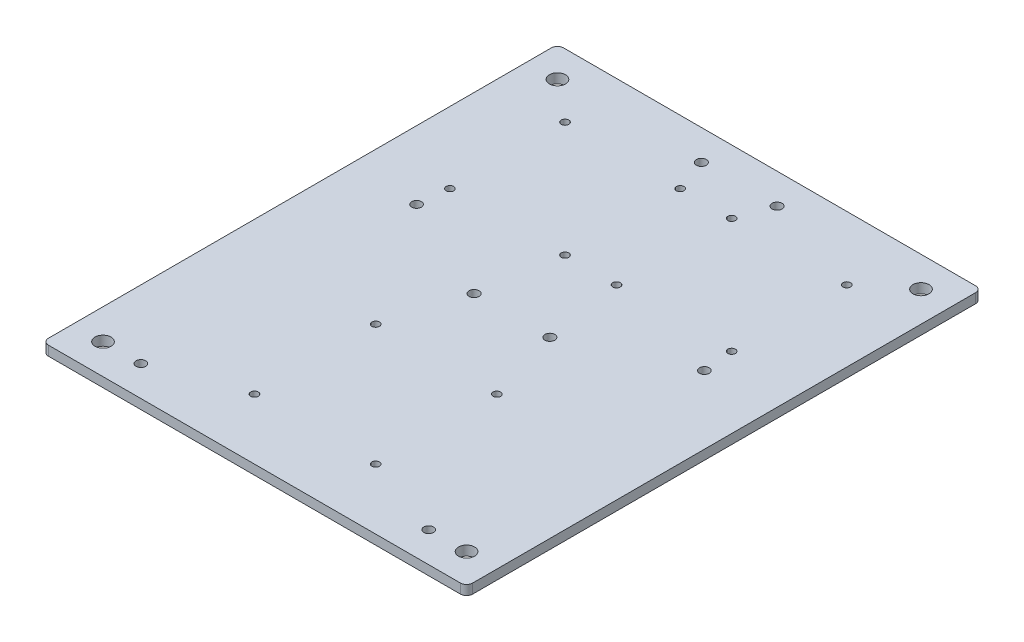
SolidWorks part; units mm, degrees
material "6061 Alloy"
ref_plane "Front Plane" through (0, 0, 0) normal (0, 0, 1) x (1, 0, 0)
ref_plane "Top Plane" through (0, 0, 0) normal (0, 1, 0) x (1, 0, 0)
ref_plane "Right Plane" through (0, 0, 0) normal (1, 0, 0) x (0, 0, -1)
sketch "Sketch1" plane through (0, 0, 0) normal (0, 1, 0) x (1, 0, 0)
  line L1 (-70, -85) -> (70, -85)
  line L2 (-70, -85) -> (-70, 85)
  line L3 (-70, 85) -> (70, 85)
  line L4 (70, -85) -> (70, 85)
  line L5 (-70, -85) -> (70, 85) construction
  line L6 (-70, 85) -> (70, -85) construction
  point P0 (0, 0)
  dimension "D1" = 170
  dimension "D2" = 140
extrude "Boss-Extrude1" add sketch "Sketch1" along normal blind 3.175
sketch "Sketch2" plane through (0, 3.175, 0) normal (0, 1, 0) x (1, 0, 0)
  line L0 (-70, -85) -> (70, -85) construction
  line L1 (-47.5, -75) -> (47.5, -75) construction
  line L2 (-47.5, -75) -> (-47.5, 16) construction
  line L3 (-47.5, 16) -> (47.5, 16) construction
  line L4 (47.5, -75) -> (47.5, 16) construction
  line L5 (-47.5, -75) -> (47.5, 16) construction
  line L6 (-47.5, 16) -> (47.5, -75) construction
  line L11 (-60, -75) -> (60, -75) construction
  line L13 (-60, -75) -> (-60, 75) construction
  line L14 (-60, 75) -> (60, 75) construction
  line L15 (60, -75) -> (60, 75) construction
  line L16 (-60, -75) -> (60, 75) construction
  line L17 (-60, 75) -> (60, -75) construction
  point P0 (0, 4.4474)
  point P6 (0, -3.3663)
  point P11 (0, 0)
  point P19 (0, -29.5)
  point P26 (0, 0)
  dimension "D1" = 95
  dimension "D2" = 91
  dimension "D3" = 150
  dimension "D4" = 120
  dimension "D5" = 10
sketch "Sketch11" plane through (0, 3.175, 0) normal (0, 1, 0) x (1, 0, 0)
  line L0 (-70, -85) -> (70, -85) construction
  line L1 (70, 85) -> (-70, 85) construction
  line L2 (-15.5, -45) -> (15.5, -45) construction
  line L3 (-12.5, 0) -> (12.5, 0) construction
  line L9 (-12.5, 0) -> (-12.5, 75) construction
  line L10 (27.5, 45) -> (-27.5, 45) construction
  line L11 (-46.5, 26) -> (-8.5, 26) construction
  line L12 (-46.5, 26) -> (-46.5, 64) construction
  line L13 (-46.5, 64) -> (-8.5, 64) construction
  line L14 (-8.5, 26) -> (-8.5, 64) construction
  line L15 (-46.5, 26) -> (-8.5, 64) construction
  line L16 (-46.5, 64) -> (-8.5, 26) construction
  line L17 (-12.5, 75) -> (12.5, 75) construction
  line L18 (8.5, 26) -> (46.5, 26) construction
  line L19 (8.5, 26) -> (8.5, 64) construction
  line L20 (8.5, 64) -> (46.5, 64) construction
  line L21 (46.5, 26) -> (46.5, 64) construction
  line L22 (8.5, 26) -> (46.5, 64) construction
  line L23 (8.5, 64) -> (46.5, 26) construction
  line L24 (-70, -45) -> (70, -45) construction
  line L25 (70, -85) -> (70, 85) construction
  line L26 (12.5, 0) -> (12.5, 75) construction
  line L27 (-12.5, 0) -> (12.5, 75) construction
  line L28 (-12.5, 75) -> (12.5, 0) construction
  line L29 (0, -60.5) -> (0, -29.5) construction
  line L31 (20, -65) -> (-20, -65) construction
  line L32 (20, -65) -> (20, -25) construction
  line L33 (20, -25) -> (-20, -25) construction
  line L34 (-20, -65) -> (-20, -25) construction
  line L35 (20, -65) -> (-20, -25) construction
  line L36 (20, -25) -> (-20, -65) construction
  point P0 (0, 37.5)
  point P9 (0, -45)
  point P16 (0, -45)
  point P17 (0, 45)
  point P23 (-27.5, 45)
  point P26 (0, 45)
  point P37 (0, -45)
  point P43 (0, -45)
  dimension "D1" = 40
  dimension "D2" = 40
  dimension "D3" = 31
  dimension "D4" = 25
  dimension "D5" = 75
  dimension "D6" = 10
  dimension "D7" = 38
  dimension "D8" = 38
  dimension "D9" = 55
  dimension "D10" = 40
hole_wizard "M3x0.5 Tapped Hole1" positions "Sketch13" profile "Sketch14" tap size "M3x0.5" standard "ANSI Metric" end condition through all
sketch "Sketch13" plane through (0, 3.175, 0) normal (0, 1, 0) x (1, 0, 0)
  point P7 (-46.5, 64)
  point P10 (-46.5, 26)
  point P13 (-8.5, 26)
  point P16 (-8.5, 64)
  point P19 (8.5, 64)
  point P22 (46.5, 64)
  point P25 (8.5, 26)
  point P28 (46.5, 26)
  point P37 (-20, -25)
  point P40 (20, -25)
  point P43 (-20, -65)
  point P46 (20, -65)
sketch "Sketch14" plane through (-46.5, 3.175, -64) normal (1, 0, 0) x (0, 0, 1)
  line L0 (0, 0) -> (0, 3.175)
  line L1 (0, 3.175) -> (1.25, 3.175)
  line L2 (1.25, 3.175) -> (1.25, 0)
  line L5 (1.25, 0) -> (0, 0)
  line L11 (0, -6.35) -> (0, 107.95) construction
  dimension "Thru Tap Drill Dia." = 2.5
  dimension "Thru Tap Drill Depth" = 3.175
cosmetic thread "Hole Thread1" parameters "D2"=3
cosmetic thread "Hole Thread2" parameters "D2"=3
cosmetic thread "Hole Thread9" parameters "D2"=3
cosmetic thread "Hole Thread10" parameters "D2"=3
cosmetic thread "Hole Thread11" parameters "D2"=3
cosmetic thread "Hole Thread12" parameters "D2"=3
cosmetic thread "Hole Thread13" parameters "D2"=3
cosmetic thread "Hole Thread14" parameters "D2"=3
cosmetic thread "Hole Thread15" parameters "D2"=3
cosmetic thread "Hole Thread16" parameters "D2"=3
cosmetic thread "Hole Thread25" parameters "D2"=3
cosmetic thread "Hole Thread26" parameters "D2"=3
hole_wizard "M3 Clearance Hole1" positions "Sketch3" profile "Sketch4" hole size "M3" standard "ANSI Metric" end condition through all
sketch "Sketch3" plane through (0, 3.175, 0) normal (0, 1, 0) x (1, 0, 0)
  point P0 (-47.5, 16)
  point P3 (47.5, 16)
  point P6 (47.5, -75)
  point P9 (-47.5, -75)
sketch "Sketch4" plane through (-47.5, 3.175, -16) normal (1, 0, 0) x (0, 0, 1)
  line L0 (0, 0) -> (0, 3.175)
  line L1 (0, 3.175) -> (1.6, 3.175)
  line L2 (1.6, 3.175) -> (1.6, 0)
  line L5 (1.6, 0) -> (0, 0)
  line L11 (0, -6.35) -> (0, 107.95) construction
  dimension "Thru Hole Dia." = 3.2
  dimension "Thru Hole Depth" = 3.175
hole_wizard "M4x0.7 Tapped Hole2" positions "Sketch15" profile "Sketch16" tap size "M4x0.7" standard "ANSI Metric" end condition through all
sketch "Sketch15" plane through (0, 3.175, 0) normal (0, 1, 0) x (1, 0, 0)
  point P0 (-12.5, 75)
  point P3 (12.5, 75)
  point P6 (-12.5, 0)
  point P9 (12.5, 0)
sketch "Sketch16" plane through (-12.5, 3.175, -75) normal (1, 0, 0) x (0, 0, 1)
  line L0 (0, 0) -> (0, 3.175)
  line L1 (0, 3.175) -> (1.65, 3.175)
  line L2 (1.65, 3.175) -> (1.65, 0)
  line L5 (1.65, 0) -> (0, 0)
  line L11 (0, -6.35) -> (0, 107.95) construction
  dimension "Thru Tap Drill Dia." = 3.3
  dimension "Thru Tap Drill Depth" = 3.175
cosmetic thread "Hole Thread21" parameters "D2"=4
cosmetic thread "Hole Thread22" parameters "D2"=4
cosmetic thread "Hole Thread23" parameters "D2"=4
cosmetic thread "Hole Thread24" parameters "D2"=4
hole_wizard "M5 Clearance Hole2" positions "Sketch9" profile "Sketch10" hole size "M5" standard "ANSI Metric" end condition through all
sketch "Sketch9" plane through (0, 3.175, 0) normal (0, 1, 0) x (1, 0, 0)
  point P0 (-60, 75)
  point P3 (60, 75)
  point P6 (-60, -75)
  point P9 (60, -75)
sketch "Sketch10" plane through (-60, 3.175, -75) normal (1, 0, 0) x (0, 0, 1)
  line L0 (0, 0) -> (0, 3.175)
  line L1 (0, 3.175) -> (2.65, 3.175)
  line L2 (2.65, 3.175) -> (2.65, 0)
  line L5 (2.65, 0) -> (0, 0)
  line L11 (0, -6.35) -> (0, 107.95) construction
  dimension "Thru Hole Dia." = 5.3
  dimension "Thru Hole Depth" = 3.175
fillet "Fillet1" radius 2 4 edges at (70, 1.5875, 85) (-70, 1.5875, 85) (70, 1.5875, -85) (-70, 1.5875, -85)
